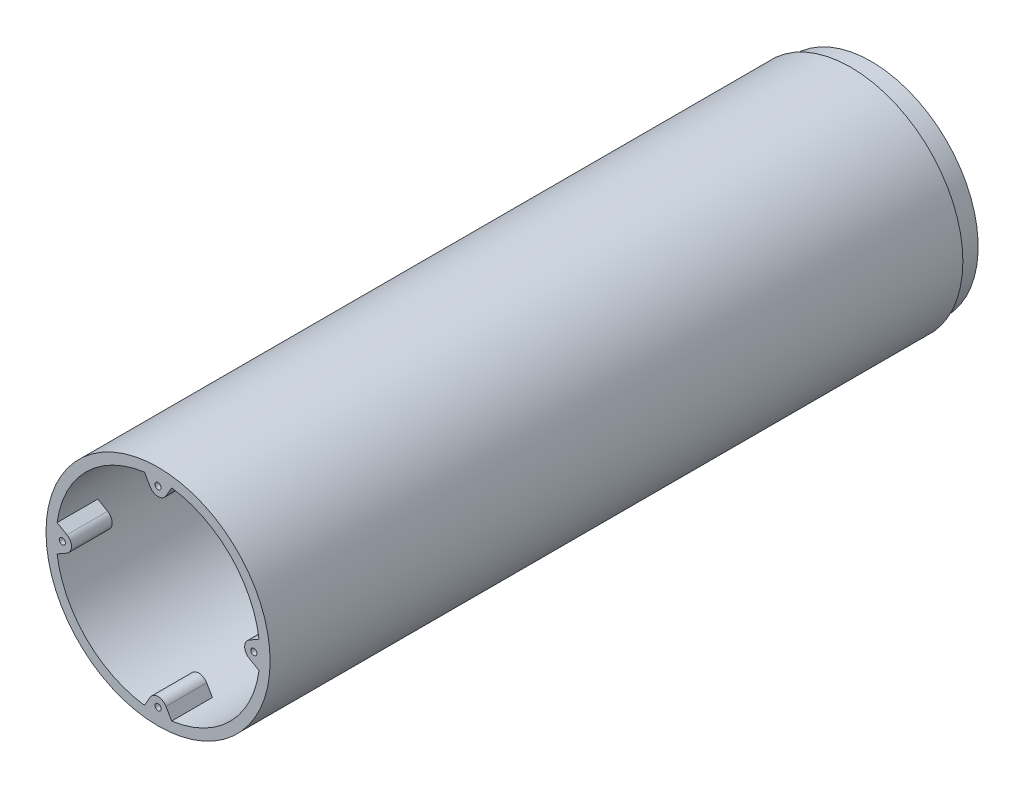
SolidWorks part; units mm, degrees
ref_plane "前视基准面" through (0, 0, 0) normal (0, 0, 1) x (1, 0, 0)
ref_plane "上视基准面" through (0, 0, 0) normal (0, 1, 0) x (1, 0, 0)
ref_plane "右视基准面" through (0, 0, 0) normal (1, 0, 0) x (0, 0, -1)
sketch "草图2" plane through (0, 0, 0) normal (0, 0, 1) x (1, 0, 0)
  circle A0 centre (0, 0) radius 55
  circle A1 centre (0, 0) radius 50
  dimension "D1" = 100
  dimension "D2" = 110
extrude "凸台-拉伸1" add sketch "草图2" along normal blind 350
sketch "草图1" plane through (0, 0, 0) normal (0, 0, 1) x (1, 0, 0)
  line L0 (0, 0) -> (-25.5751, 0) construction
  line L1 (-49.5531, 6.6702) -> (-44.75, 3.8971)
  line L2 (-49.5531, -6.6702) -> (-44.75, -3.8971)
  line L3 (0, 0) -> (-6.6702, 49.5531) construction
  line L4 (-49.5531, -6.6702) -> (0, 0) construction
  line L5 (6.6702, 49.5531) -> (3.8971, 44.75)
  line L6 (-6.6702, 49.5531) -> (-3.8971, 44.75)
  line L7 (49.5531, -6.6702) -> (44.75, -3.8971)
  line L8 (49.5531, 6.6702) -> (44.75, 3.8971)
  line L9 (-6.6702, -49.5531) -> (-3.8971, -44.75)
  line L10 (6.6702, -49.5531) -> (3.8971, -44.75)
  circle A0 centre (0, 0) radius 50 construction
  circle A1 centre (0, 0) radius 55
  circle A2 centre (-47, 0) radius 1.5
  arc A4 (-44.75, 3.8971) -> (-44.75, -3.8971) centre (-47, 0) cw
  arc A5 (-49.5531, 6.6702) -> (-6.6702, 49.5531) centre (0, 0) cw
  circle A6 centre (0, 47) radius 1.5
  arc A7 (3.8971, 44.75) -> (-3.8971, 44.75) centre (0, 47) cw
  arc A8 (6.6702, 49.5531) -> (49.5531, 6.6702) centre (0, 0) cw
  circle A9 centre (47, 0) radius 1.5
  arc A10 (44.75, -3.8971) -> (44.75, 3.8971) centre (47, 0) cw
  arc A11 (49.5531, -6.6702) -> (6.6702, -49.5531) centre (0, 0) cw
  circle A12 centre (0, -47) radius 1.5
  arc A13 (-3.8971, -44.75) -> (3.8971, -44.75) centre (0, -47) cw
  arc A14 (-6.6702, -49.5531) -> (-49.5531, -6.6702) centre (0, 0) cw
  circle A15 centre (0, 0) radius 50 construction
  circle A16 centre (0, 0) radius 55 construction
  point P38 (0, 0)
  dimension "D3" = 47
  dimension "D4" = 3
  dimension "D5" = 3
  dimension "D7" = 90
  dimension "D8" = 4
  dimension "D6" = 30
extrude "凸台-拉伸2" add sketch "草图1" along normal blind 20 contours A1 A12 A9 A6 A2 L9 A14 L2 A4 L1 A5 L6 A7 L5 A8 L8 A10 L7 A11 L10 A13
sketch "草图3" plane through (0, 0, 20) normal (0, 0, 1) x (1, 0, 0)
  line L0 (-1.5877, 44.25) -> (1.5877, 44.25)
  line L1 (-44.25, -1.5877) -> (-44.25, 1.5877)
  line L2 (-44.25, 1.5877) -> (-47, 3.1754)
  line L3 (-47, 3.1754) -> (-49.75, 1.5877)
  line L4 (-49.75, 1.5877) -> (-49.75, -1.5877)
  line L5 (-49.75, -1.5877) -> (-47, -3.1754)
  line L6 (-47, -3.1754) -> (-44.25, -1.5877)
  line L7 (1.5877, 44.25) -> (3.1754, 47)
  line L8 (3.1754, 47) -> (1.5877, 49.75)
  line L9 (1.5877, 49.75) -> (-1.5877, 49.75)
  line L10 (-1.5877, 49.75) -> (-3.1754, 47)
  line L11 (-3.1754, 47) -> (-1.5877, 44.25)
  line L12 (44.25, 1.5877) -> (44.25, -1.5877)
  line L13 (44.25, -1.5877) -> (47, -3.1754)
  line L14 (47, -3.1754) -> (49.75, -1.5877)
  line L15 (49.75, -1.5877) -> (49.75, 1.5877)
  line L16 (49.75, 1.5877) -> (47, 3.1754)
  line L17 (47, 3.1754) -> (44.25, 1.5877)
  line L18 (1.5877, -44.25) -> (-1.5877, -44.25)
  line L19 (-1.5877, -44.25) -> (-3.1754, -47)
  line L20 (-3.1754, -47) -> (-1.5877, -49.75)
  line L21 (-1.5877, -49.75) -> (1.5877, -49.75)
  line L22 (1.5877, -49.75) -> (3.1754, -47)
  line L23 (3.1754, -47) -> (1.5877, -44.25)
  circle A0 centre (-47, 0) radius 2.75 construction
  circle A1 centre (0, 47) radius 2.75 construction
  circle A2 centre (47, 0) radius 2.75 construction
  circle A3 centre (0, -47) radius 2.75 construction
  point P36 (0, 0)
  dimension "D1" = 5.5
  dimension "D2" = 4
extrude "切除-拉伸1" cut sketch "草图3" against normal blind 2
ref_plane "基准面4" through (0, 0, 175) normal (0, 0, -1) x (-1, 0, 0)
mirror "镜向1" about plane through (0, 0, 175) normal (0, 0, -1) of "切除-拉伸1", "凸台-拉伸2"
sketch "草图4" plane through (0, 0, 0) normal (0, 0, -1) x (-1, 0, 0)
  circle A0 centre (0, 0) radius 55
  circle A1 centre (0, 0) radius 52.5
  circle A2 centre (0, 0) radius 55 construction
  dimension "D1" = 2.5
extrude "切除-拉伸2" cut sketch "草图4" against normal blind 10
